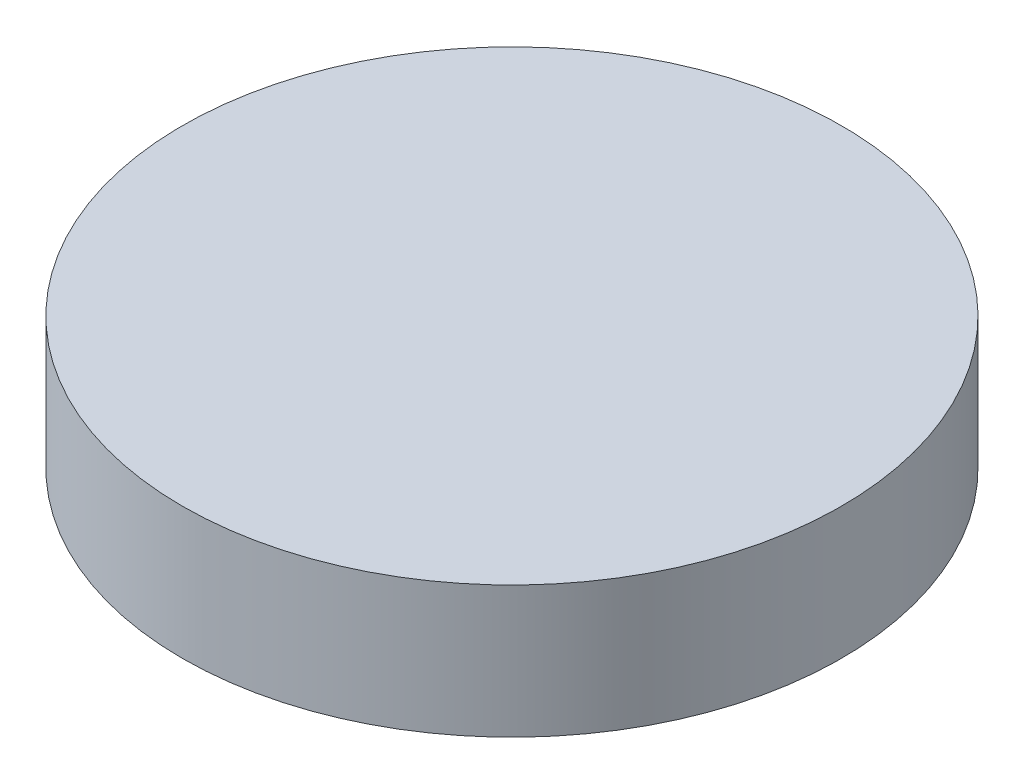
SolidWorks part; units mm, degrees
ref_plane "Front Plane" through (0, 0, 0) normal (0, 0, 1) x (1, 0, 0)
ref_plane "Top Plane" through (0, 0, 0) normal (0, 1, 0) x (1, 0, 0)
ref_plane "Right Plane" through (0, 0, 0) normal (1, 0, 0) x (0, 0, -1)
sketch "Sketch3" plane through (0, 0, 0) normal (0, 1, 0) x (1, 0, 0)
  line L1 (-25.4, -25.4) -> (25.4, -25.4) construction
  line L2 (-25.4, -25.4) -> (-25.4, 25.4) construction
  line L3 (-25.4, 25.4) -> (25.4, 25.4) construction
  line L4 (25.4, -25.4) -> (25.4, 25.4) construction
  line L5 (-25.4, -25.4) -> (25.4, 25.4) construction
  line L6 (-25.4, 25.4) -> (25.4, -25.4) construction
  circle A0 centre (0, 0) radius 25.4
  point P0 (0, 0)
  dimension "D1" = 50.8
  dimension "D2" = 50.8
extrude "Boss-Extrude1" add sketch "Sketch3" along normal blind 10.16
sketch "Sketch4" plane through (0, 10.16, 0) normal (0, 1, 0) x (1, 0, 0)
  circle A0 centre (0, 0) radius 6.35
  circle A1 centre (0, 0) radius 6.35
  dimension "D1" = 12.7
sketch "Sketch5" plane through (0, 0, 0) normal (0, -1, 0) x (1, 0, 0)
  circle A0 centre (0, 0) radius 22.2498
extrude "Cut-Extrude1" cut sketch "Sketch5" against normal blind 7.62
